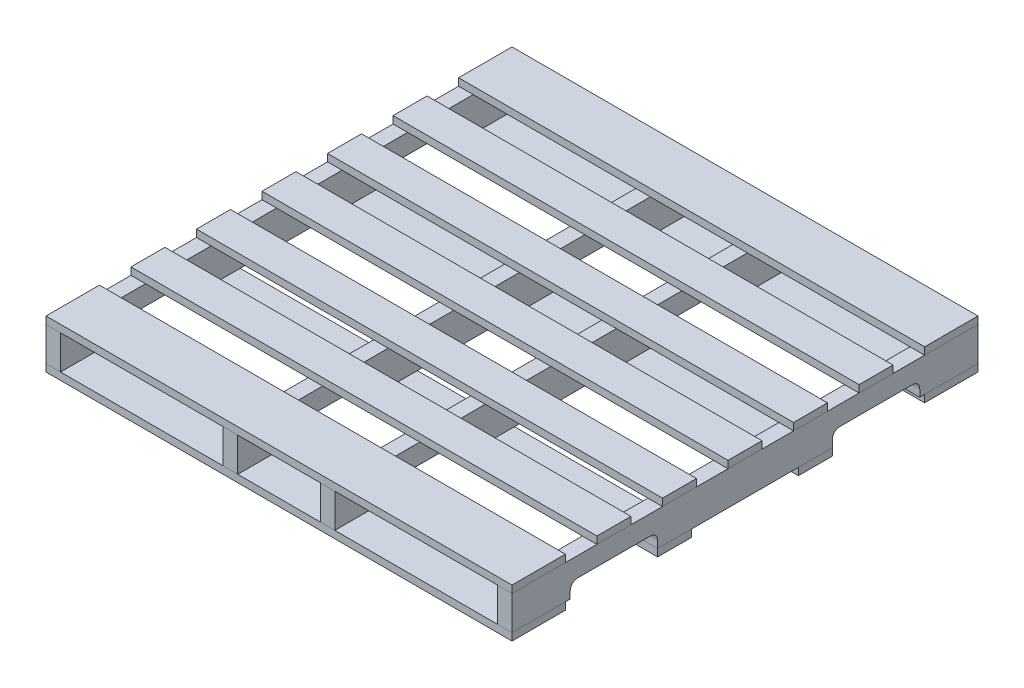
SolidWorks part; units mm, degrees
ref_plane "Front Plane" through (0, 0, 0) normal (0, 0, 1) x (1, 0, 0)
ref_plane "Top Plane" through (0, 0, 0) normal (0, 1, 0) x (1, 0, 0)
ref_plane "Right Plane" through (0, 0, 0) normal (1, 0, 0) x (0, 0, -1)
sketch "Sketch1" plane through (0, 0, 0) normal (0, 0, 1) x (1, 0, 0)
  line L0 (-609.6, 0) -> (609.6, 0) construction
  line L5 (-609.6, 63.5) -> (-609.6, -63.5) construction
  line L6 (609.6, 63.5) -> (609.6, -63.5) construction
  line L11 (-609.6, -63.5) -> (609.6, -63.5) construction
  line L12 (-609.6, 63.5) -> (609.6, 63.5) construction
  line L13 (-571.5, 63.5) -> (-571.5, -63.5) construction
  line L15 (-146.05, 63.5) -> (-146.05, -63.5) construction
  line L16 (-107.95, -63.5) -> (-107.95, 63.5) construction
  line L17 (0, 63.5) -> (0, -63.5) construction
  line L18 (-609.6, 0) -> (-571.5, 0)
  line L19 (-146.05, 0) -> (-107.95, 0)
  line L21 (571.5, 63.5) -> (571.5, -63.5) construction
  line L22 (-609.6, 44.45) -> (609.6, 44.45) construction
  line L23 (-609.6, -44.45) -> (609.6, -44.45) construction
  line L24 (107.95, 63.5) -> (146.05, 63.5)
  line L25 (107.95, 63.5) -> (107.95, -63.5)
  line L26 (107.95, -63.5) -> (146.05, -63.5)
  line L27 (146.05, 63.5) -> (146.05, -63.5)
  point P3 (0, 0)
  point P6 (-609.6, 0)
  point P9 (609.6, 0)
  point P23 (0, 0)
  dimension "D1" = 38.1
  dimension "Width" = 1219.2
  dimension "Height" = 127
  dimension "Maximum Fork Width" = 425.45
  dimension "D3" = 19.05
  dimension "Maximum Fork Height" = 88.9
sketch "Sketch2" plane through (0, 0, 0) normal (1, 0, 0) x (0, 0, -1)
  line L0 (609.6, 0) -> (-609.6, 0) construction
  point P4 (0, 0)
  dimension "Depth" = 1219.2
sketch "Sketch3" plane through (0, 0, 0) normal (0, 0, 1) x (1, 0, 0)
  line L0 (571.5, 63.5) -> (571.5, -63.5) construction
  line L5 (146.05, 63.5) -> (146.05, -63.5) construction
  line L6 (-571.5, 63.5) -> (-571.5, -63.5) construction
  line L7 (-609.6, 44.45) -> (-571.5, 44.45)
  line L8 (-609.6, 44.45) -> (-609.6, -44.45)
  line L9 (-609.6, -44.45) -> (-571.5, -44.45)
  line L10 (-571.5, 44.45) -> (-571.5, -44.45)
  line L11 (-609.6, 44.45) -> (609.6, 44.45) construction
  line L12 (146.05, 44.45) -> (107.95, 44.45)
  line L13 (-609.6, -44.45) -> (609.6, -44.45) construction
  line L14 (571.5, 44.45) -> (609.6, 44.45)
  line L15 (571.5, 44.45) -> (571.5, -44.45)
  line L16 (571.5, -44.45) -> (609.6, -44.45)
  line L17 (609.6, 44.45) -> (609.6, -44.45)
  line L18 (-609.6, 63.5) -> (-609.6, -63.5) construction
  line L19 (146.05, 44.45) -> (146.05, -44.45)
  line L20 (-146.05, 63.5) -> (-146.05, -63.5) construction
  line L21 (-146.05, 44.45) -> (-107.95, 44.45)
  line L22 (-146.05, 44.45) -> (-146.05, -44.45)
  line L23 (-146.05, -44.45) -> (-107.95, -44.45)
  line L24 (-107.95, 44.45) -> (-107.95, -44.45)
  line L25 (-107.95, -63.5) -> (-107.95, 63.5) construction
  line L26 (146.05, -44.45) -> (107.95, -44.45)
  line L27 (107.95, 44.45) -> (107.95, -44.45)
  line L28 (107.95, 63.5) -> (107.95, -63.5) construction
extrude "Boss-Extrude1" add sketch "Sketch3" along normal up to vertex (609.6 mm away) and the other way up to vertex (609.6 mm away) up to point (0, 0, 609.6) other way up to point (0, 0, -609.6)
sketch "Sketch4" plane through (0, 44.45, 0) normal (0, 1, 0) x (1, 0, 0)
  line L0 (609.6, -609.6) -> (609.6, 609.6) construction
  line L1 (-609.6, -609.6) -> (609.6, -609.6)
  line L2 (-609.6, -609.6) -> (-609.6, -469.9)
  line L3 (-609.6, -469.9) -> (609.6, -469.9)
  line L4 (609.6, -609.6) -> (609.6, -469.9)
  line L22 (-609.6, -609.6) -> (-609.6, 609.6) construction
  line L26 (-609.6, 469.9) -> (609.6, 469.9)
  line L27 (-609.6, 469.9) -> (-609.6, 609.6)
  line L28 (-609.6, 609.6) -> (609.6, 609.6)
  line L29 (609.6, 469.9) -> (609.6, 609.6)
  line L31 (-609.6, -387.35) -> (609.6, -387.35)
  line L32 (-609.6, -387.35) -> (-609.6, -298.45)
  line L33 (-609.6, -298.45) -> (609.6, -298.45)
  line L34 (609.6, -387.35) -> (609.6, -298.45)
  line L35 (-609.6, -215.9) -> (609.6, -215.9)
  line L36 (-609.6, -215.9) -> (-609.6, -127)
  line L37 (-609.6, -127) -> (609.6, -127)
  line L38 (609.6, -215.9) -> (609.6, -127)
  line L39 (-609.6, 387.35) -> (609.6, 387.35)
  line L40 (-609.6, 387.35) -> (-609.6, 298.45)
  line L41 (-609.6, 298.45) -> (609.6, 298.45)
  line L42 (609.6, 387.35) -> (609.6, 298.45)
  line L43 (-609.6, 215.9) -> (609.6, 215.9)
  line L44 (-609.6, 215.9) -> (-609.6, 127)
  line L45 (-609.6, 127) -> (609.6, 127)
  line L46 (609.6, 215.9) -> (609.6, 127)
  line L47 (-609.6, 44.45) -> (609.6, 44.45)
  line L48 (-609.6, 44.45) -> (-609.6, -44.45)
  line L49 (-609.6, -44.45) -> (609.6, -44.45)
  line L50 (609.6, 44.45) -> (609.6, -44.45)
  dimension "D1" = 139.7
  dimension "D3" = 88.9
  dimension "D2" = 82.55
  dimension "D4" = 82.55
  dimension "D5" = 82.55
  dimension "D6" = 82.55
  dimension "D7" = 82.55
extrude "Boss-Extrude2" add sketch "Sketch4" along normal up to vertex (19.05 mm away) separate body up to point (-609.6, 63.5, 0)
sketch "Sketch5" plane through (0, -44.45, 0) normal (0, -1, 0) x (1, 0, 0)
  line L0 (609.6, 609.6) -> (609.6, -609.6) construction
  line L1 (-609.6, 609.6) -> (609.6, 609.6)
  line L2 (-609.6, 609.6) -> (-609.6, 469.9)
  line L3 (-609.6, 469.9) -> (609.6, 469.9)
  line L4 (609.6, 609.6) -> (609.6, 469.9)
  line L5 (-609.6, -609.6) -> (609.6, -609.6)
  line L6 (-609.6, -609.6) -> (-609.6, -469.9)
  line L7 (-609.6, -469.9) -> (609.6, -469.9)
  line L8 (609.6, -609.6) -> (609.6, -469.9)
  line L15 (-609.6, 609.6) -> (-609.6, -609.6) construction
  line L16 (-609.6, 609.6) -> (-609.6, 469.9) construction
  line L17 (609.6, 609.6) -> (609.6, 469.9) construction
  line L18 (-609.6, 228.6) -> (609.6, 228.6)
  line L19 (-609.6, 228.6) -> (-609.6, 139.7)
  line L20 (-609.6, 139.7) -> (609.6, 139.7)
  line L21 (609.6, 228.6) -> (609.6, 139.7)
  line L22 (-609.6, -228.6) -> (609.6, -228.6)
  line L23 (-609.6, -228.6) -> (-609.6, -139.7)
  line L24 (-609.6, -139.7) -> (609.6, -139.7)
  line L25 (609.6, -228.6) -> (609.6, -139.7)
  dimension "D1" = 241.3
  dimension "D2" = 241.3
  dimension "D3" = 88.9
  dimension "D4" = 139.7
extrude "Boss-Extrude3" add sketch "Sketch5" along normal up to vertex (19.05 mm away) separate body up to point (-609.6, -63.5, 0)
sketch "Sketch8" plane through (609.6, 0, 0) normal (1, 0, 0) x (0, 0, -1)
  line L1 (-228.6, -44.45) -> (-457.2, -44.45)
  line L2 (-228.6, -44.45) -> (-228.6, -25.4)
  line L3 (-247.65, -6.35) -> (-438.15, -6.35)
  line L4 (-457.2, -44.45) -> (-457.2, -25.4)
  line L5 (228.6, -44.45) -> (457.2, -44.45)
  line L6 (228.6, -44.45) -> (228.6, -25.4)
  line L7 (247.65, -6.35) -> (438.15, -6.35)
  line L8 (457.2, -44.45) -> (457.2, -25.4)
  arc A0 (438.15, -6.35) -> (457.2, -25.4) centre (438.15, -25.4) cw
  arc A1 (228.6, -25.4) -> (247.65, -6.35) centre (247.65, -25.4) cw
  arc A2 (-228.6, -25.4) -> (-247.65, -6.35) centre (-247.65, -25.4) ccw
  arc A3 (-438.15, -6.35) -> (-457.2, -25.4) centre (-438.15, -25.4) ccw
  point P18 (-457.2, -6.35)
  dimension "D3" = 19.05
  dimension "D1" = 38.1
  dimension "D2" = 228.6
extrude "Cut-Extrude2" cut sketch "Sketch8" against normal through all both and the other way through all
sketch "Sketch7" plane through (0, 0, 0) normal (0, 1, 0) x (1, 0, 0)
  line L0 (0, 609.6) -> (609.6, 609.6) construction
  line L2 (609.6, 609.6) -> (609.6, 0) construction
  line L3 (609.6, 0) -> (609.6, -609.6) construction
  line L4 (609.6, -609.6) -> (0, -609.6) construction
  line L5 (-609.6, -609.6) -> (609.6, -609.6) construction
  line L6 (-609.6, 609.6) -> (0, 609.6) construction
